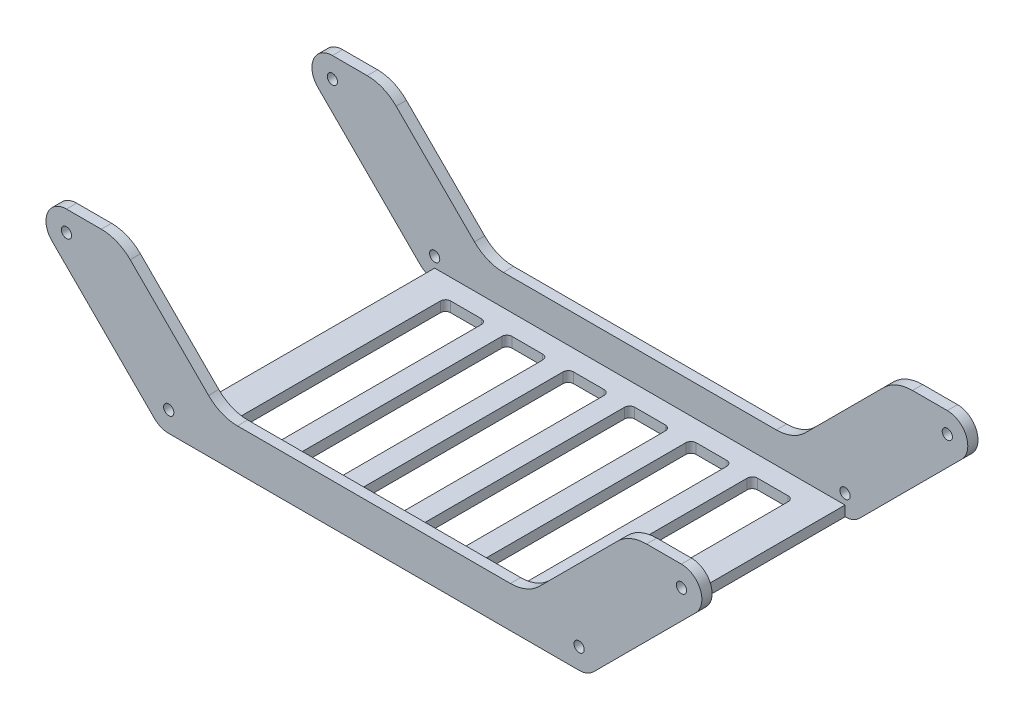
SolidWorks part; units mm, degrees
ref_plane "Front Plane" through (0, 0, 0) normal (0, 0, 1) x (1, 0, 0)
ref_plane "Top Plane" through (0, 0, 0) normal (0, 1, 0) x (1, 0, 0)
ref_plane "Right Plane" through (0, 0, 0) normal (1, 0, 0) x (0, 0, -1)
sketch "Sketch1" plane through (0, 0, 0) normal (0, 0, 1) x (1, 0, 0)
  line L0 (401.25, 0) -> (-401.25, 0) construction
  line L1 (-401.25, 0) -> (-601.25, 200) construction
  line L2 (-601.25, 200) -> (601.25, 200) construction
  line L3 (601.25, 200) -> (401.25, 0) construction
  line L4 (0, 200) -> (0, 240) construction
  line L5 (0, 0) -> (0, -40) construction
  line L6 (-401.25, -40) -> (401.25, -40)
  line L7 (-429.5343, -28.2843) -> (-629.5343, 171.7157)
  line L8 (-601.25, 240) -> (-533.1371, 240)
  line L9 (629.5343, 171.7157) -> (429.5343, -28.2843)
  line L10 (0, 0) -> (0, 40) construction
  line L11 (-266.8629, 40) -> (266.8629, 40)
  line L12 (-476.5685, 216.5685) -> (-323.4315, 63.4315)
  line L13 (323.4315, 63.4315) -> (476.5685, 216.5685)
  line L14 (533.1371, 240) -> (601.25, 240)
  circle A1 centre (601.25, 200) radius 10
  circle A2 centre (401.25, 0) radius 10
  circle A3 centre (-401.25, 0) radius 10
  circle A5 centre (-601.25, 200) radius 10
  arc A6 (-429.5343, -28.2843) -> (-401.25, -40) centre (-401.25, 0) ccw
  arc A7 (-601.25, 240) -> (-629.5343, 171.7157) centre (-601.25, 200) ccw
  arc A8 (401.25, -40) -> (429.5343, -28.2843) centre (401.25, 0) ccw
  arc A9 (629.5343, 171.7157) -> (601.25, 240) centre (601.25, 200) ccw
  arc A10 (476.5685, 216.5685) -> (533.1371, 240) centre (533.1371, 160) cw
  arc A11 (323.4315, 63.4315) -> (266.8629, 40) centre (266.8629, 120) cw
  arc A12 (-323.4315, 63.4315) -> (-266.8629, 40) centre (-266.8629, 120) ccw
  arc A13 (-476.5685, 216.5685) -> (-533.1371, 240) centre (-533.1371, 160) ccw
  point P4 (0, 0)
  point P22 (0, -40)
  point P32 (0, 40)
  point P36 (500, 240)
  point P39 (300, 40)
  point P42 (-300, 40)
  dimension "D5" = 20
  dimension "D6" = 20
  dimension "D7" = 20
  dimension "D8" = 20
  dimension "D11" = 80
  dimension "D12" = 80
  dimension "D18" = 80
  dimension "D1" = 802.5
  dimension "D2" = 45
  dimension "D3" = 45
  dimension "D4" = 200
  dimension "D9" = 40
  dimension "D10" = 40
  dimension "D13" = 40
  dimension "D14" = 45
  dimension "D15" = 45
  dimension "D16" = 300
  dimension "D17" = 300
extrude "Boss-Extrude1" add sketch "Sketch1" along normal blind 20
sketch "Sketch2" plane through (0, -40, 0) normal (0, -1, 0) x (1, 0, 0)
  line L0 (-401.25, 10) -> (-212.386, 10)
  line L5 (-401.25, 20) -> (-401.25, 0) construction
  line L6 (-401.25, -500) -> (401.25, -500)
  line L7 (401.25, 0) -> (401.25, -500)
  line L8 (-401.25, 0) -> (401.25, 0)
  line L9 (-401.25, 0) -> (-401.25, -500)
  line L10 (-401.25, 0) -> (401.25, 0) construction
  line L12 (-330, -460) -> (-270, -460)
  line L13 (-340, -450) -> (-340, -50)
  line L14 (-330, -40) -> (-270, -40)
  line L15 (-260, -450) -> (-260, -50)
  line L39 (-220, -450) -> (-220, -50)
  line L40 (-210, -460) -> (-150, -460)
  line L41 (-140, -450) -> (-140, -50)
  line L42 (-210, -40) -> (-150, -40)
  line L43 (-100, -450) -> (-100, -50)
  line L44 (-90, -460) -> (-30, -460)
  line L45 (-20, -450) -> (-20, -50)
  line L46 (-90, -40) -> (-30, -40)
  line L47 (20, -450) -> (20, -50)
  line L48 (30, -460) -> (90, -460)
  line L49 (100, -450) -> (100, -50)
  line L50 (30, -40) -> (90, -40)
  line L51 (140, -450) -> (140, -50)
  line L52 (150, -460) -> (210, -460)
  line L53 (220, -450) -> (220, -50)
  line L54 (150, -40) -> (210, -40)
  line L55 (260, -450) -> (260, -50)
  line L56 (270, -460) -> (330, -460)
  line L57 (340, -450) -> (340, -50)
  line L58 (270, -40) -> (330, -40)
  arc A0 (-330, -460) -> (-340, -450) centre (-330, -450) cw
  arc A1 (-270, -460) -> (-260, -450) centre (-270, -450) ccw
  arc A2 (-270, -40) -> (-260, -50) centre (-270, -50) cw
  arc A3 (-340, -50) -> (-330, -40) centre (-330, -50) cw
  arc A4 (-220, -50) -> (-210, -40) centre (-210, -50) cw
  arc A5 (-210, -460) -> (-220, -450) centre (-210, -450) cw
  arc A6 (-150, -460) -> (-140, -450) centre (-150, -450) ccw
  arc A7 (-150, -40) -> (-140, -50) centre (-150, -50) cw
  arc A8 (-100, -50) -> (-90, -40) centre (-90, -50) cw
  arc A9 (-90, -460) -> (-100, -450) centre (-90, -450) cw
  arc A10 (-30, -460) -> (-20, -450) centre (-30, -450) ccw
  arc A11 (-30, -40) -> (-20, -50) centre (-30, -50) cw
  arc A12 (20, -50) -> (30, -40) centre (30, -50) cw
  arc A13 (30, -460) -> (20, -450) centre (30, -450) cw
  arc A14 (90, -460) -> (100, -450) centre (90, -450) ccw
  arc A15 (90, -40) -> (100, -50) centre (90, -50) cw
  arc A16 (140, -50) -> (150, -40) centre (150, -50) cw
  arc A17 (150, -460) -> (140, -450) centre (150, -450) cw
  arc A18 (210, -460) -> (220, -450) centre (210, -450) ccw
  arc A19 (210, -40) -> (220, -50) centre (210, -50) cw
  arc A20 (260, -50) -> (270, -40) centre (270, -50) cw
  arc A21 (270, -460) -> (260, -450) centre (270, -450) cw
  arc A22 (330, -460) -> (340, -450) centre (330, -450) ccw
  arc A23 (330, -40) -> (340, -50) centre (330, -50) cw
  point P18 (0, -500)
  line M5 (-401.25, 0) -> (401.25, 0)
  dimension "D10" = 10
  dimension "D1" = 500
  dimension "D2" = 0
  dimension "D3" = 500
  dimension "D4" = 61.25
  dimension "D5" = 40
  dimension "D6" = 40
  dimension "D7" = 80
  dimension "D8" = 6
extrude "Boss-Extrude3" add sketch "Sketch2" against normal blind 20 contours L9 L6 L7 M5
ref_plane "Plane1" through (0, 0, -250) normal (0, 0, -1) x (-1, 0, 0)
mirror "Mirror1" about plane through (0, 0, -250) normal (0, 0, -1) of "Boss-Extrude1"
